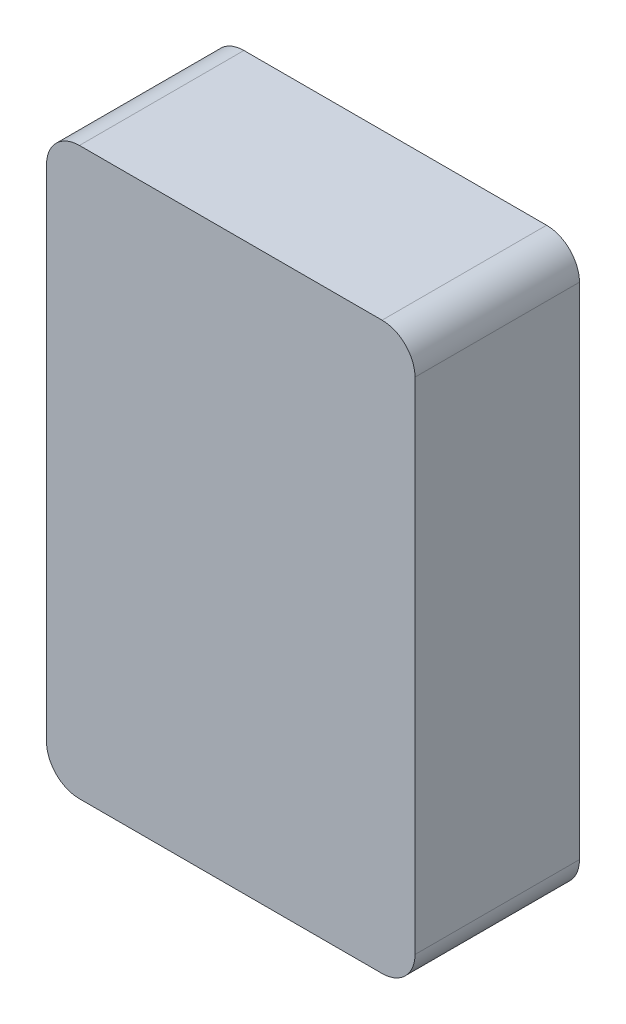
SolidWorks part; units mm, degrees
ref_plane "Front Plane" through (0, 0, 0) normal (0, 0, 1) x (1, 0, 0)
ref_plane "Top Plane" through (0, 0, 0) normal (0, 1, 0) x (1, 0, 0)
ref_plane "Right Plane" through (0, 0, 0) normal (1, 0, 0) x (0, 0, -1)
sketch "Sketch1" plane through (0, 0, 0) normal (0, 0, 1) x (1, 0, 0)
  line L1 (-23, 43) -> (23, 43)
  line L2 (-28, 38) -> (-28, -38)
  line L3 (-23, -43) -> (23, -43)
  line L4 (28, 38) -> (28, -38)
  line L5 (-28, 43) -> (28, -43) construction
  line L6 (-28, -43) -> (28, 43) construction
  arc A0 (-28, -38) -> (-23, -43) centre (-23, -38) ccw
  arc A1 (23, -43) -> (28, -38) centre (23, -38) ccw
  arc A2 (23, 43) -> (28, 38) centre (23, 38) cw
  arc A3 (-23, 43) -> (-28, 38) centre (-23, 38) ccw
  point P0 (0, 0)
  dimension "D3" = 5
  dimension "D1" = 56
  dimension "D2" = 86
extrude "Boss-Extrude1" add sketch "Sketch1" along normal blind 25
